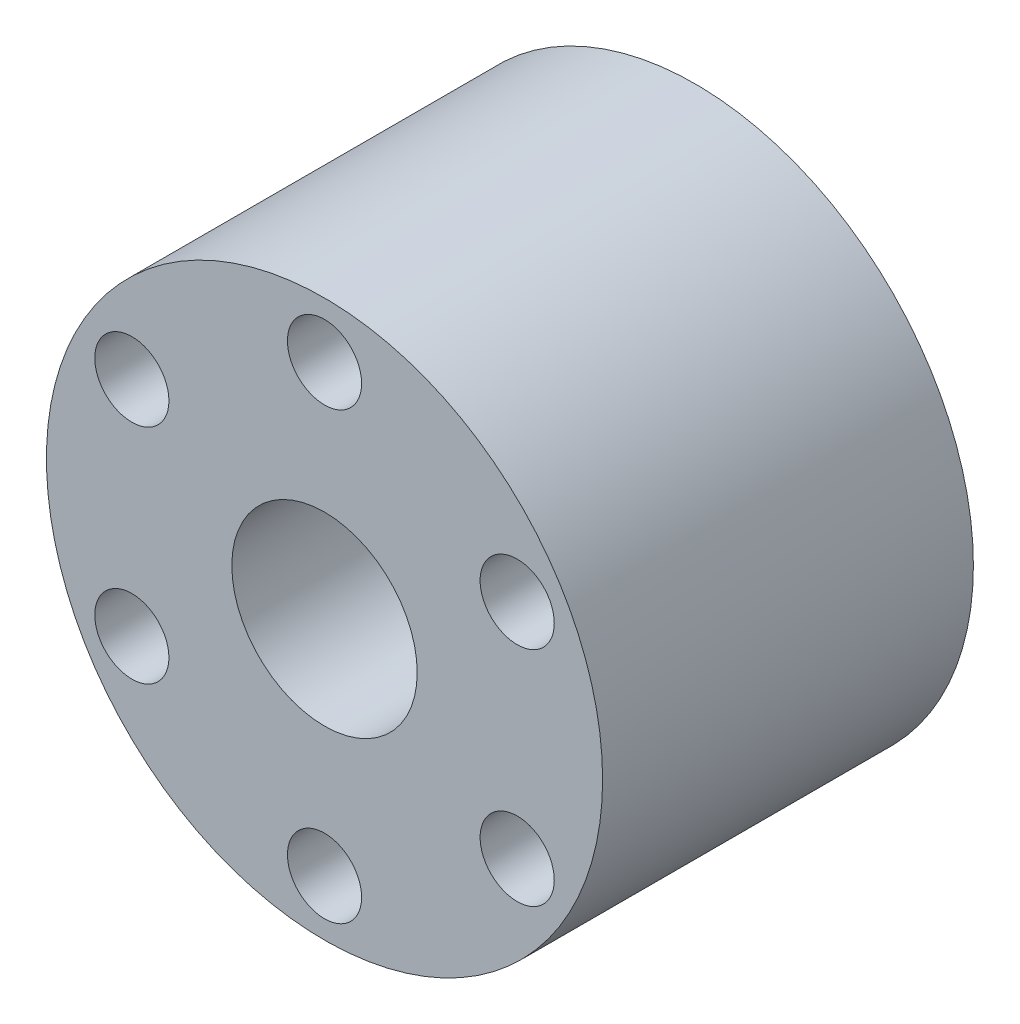
SolidWorks part; units mm, degrees
material "6061 Alloy"
ref_plane "Front Plane" through (0, 0, 0) normal (0, 0, 1) x (1, 0, 0)
ref_plane "Top Plane" through (0, 0, 0) normal (0, 1, 0) x (1, 0, 0)
ref_plane "Right Plane" through (0, 0, 0) normal (1, 0, 0) x (0, 0, -1)
sketch "Sketch1" plane through (0, 0, 0) normal (0, 0, 1) x (1, 0, 0)
  circle A0 centre (0, 0) radius 15
  dimension "D1" = 30
extrude "Boss-Extrude1" add sketch "Sketch1" along normal blind 20
sketch "Sketch2" plane through (0, 0, 20) normal (0, 0, 1) x (1, 0, 0)
  line L0 (0, 0) -> (0, 16.0428) construction
  circle A0 centre (0, 0) radius 5
  circle A1 centre (0, 12) radius 2
  circle A2 centre (10.3923, 6) radius 2
  circle A3 centre (10.3923, -6) radius 2
  circle A4 centre (0, -12) radius 2
  circle A5 centre (-10.3923, -6) radius 2
  circle A6 centre (-10.3923, 6) radius 2
  circle A7 centre (0, 0) radius 15 construction
  point P18 (0, 0)
  dimension "D1" = 10
  dimension "D2" = 4
  dimension "D4" = 12
  dimension "D3" = 6
extrude "Cut-Extrude1" cut sketch "Sketch2" against normal through all
